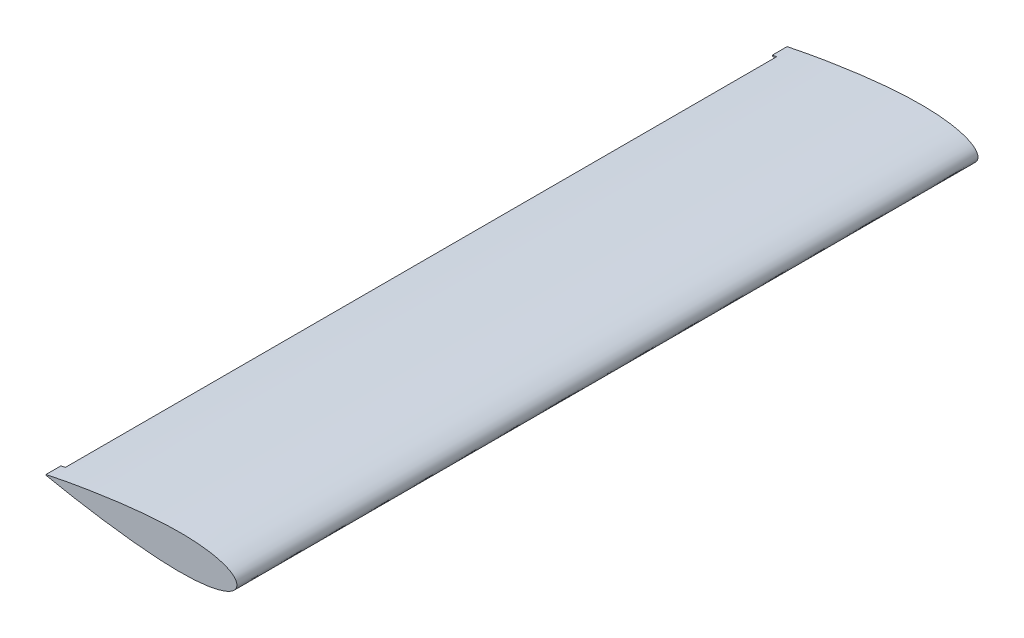
SolidWorks part; units mm, degrees
ref_plane "Alzado" through (0, 0, 0) normal (0, 0, 1) x (1, 0, 0)
ref_plane "Planta" through (0, 0, 0) normal (0, 1, 0) x (1, 0, 0)
ref_plane "Vista lateral" through (0, 0, 0) normal (1, 0, 0) x (0, 0, -1)
sketch "Croquis1" plane through (0, 0, 0) normal (0, 0, 1) x (1, 0, 0)
  line L0 (0, 0) -> (0, -23.5) construction
  line L1 (0, 0) -> (-16, 0) construction
  line L2 (-14.2698, -25.6618) -> (-26, -25.6618)
  line L3 (-26, -25.6618) -> (-26, -33.5)
  line L4 (-26, -33.5) -> (16, -33.5)
  line L5 (16, -33.5) -> (16, 3.8445)
  line L6 (16, 3.8445) -> (-14.2698, 3.8445)
  line L8 (-14.2698, -6.2762) -> (-14.2698, -25.6618)
  line L9 (-14.2698, 3.8445) -> (-26, 3.8445)
  line L10 (-26, 3.8445) -> (-26, -6.2762)
  line L11 (-26, -6.2762) -> (-14.2698, -6.2762)
  circle A0 centre (0, 0) radius 1.5
  dimension "D1" = 3
  dimension "D4" = 16
  dimension "D2" = 23.5
  dimension "D3" = 16
  dimension "D5" = 10
  dimension "D6" = 42
curve "Curva2"
  spline degree 3 poles (266, 0.503, 0) (261.5688, 1.4191, 0) (252.7164, 3.2493, 0) (234.9955, 6.6448, 0) (212.8433, 10.5485, 0) (186.2398, 14.7043, 0) (159.6407, 18.3128, 0) (133.0409, 21.2624, 0) (106.4348, 23.353, 0) (84.237, 24.0962, 0) (66.4893, 23.7999, 0) (53.1677, 23.0109, 0) (39.8211, 21.4881, 0) (28.7128, 19.3599, 0) (19.853, 16.8285, 0) (13.0874, 14.2708, 0) (7.4196, 11.1923, 0) (2.2073, 6.9321, 0) (-1.4404, 0, 0) (2.2073, -6.9321, 0) (7.4196, -11.1923, 0) (13.0874, -14.2708, 0) (19.853, -16.8285, 0) (28.7128, -19.3599, 0) (39.8211, -21.4881, 0) (53.1677, -23.0109, 0) (66.4893, -23.7999, 0) (84.237, -24.0962, 0) (106.4348, -23.353, 0) (133.0409, -21.2624, 0) (159.6407, -18.3128, 0) (186.2398, -14.7043, 0) (212.8433, -10.5485, 0) (234.9955, -6.6448, 0) (252.7164, -3.2493, 0) (261.5688, -1.4191, 0) (266, -0.503, 0) knots 0 0 0 0 0.024604 0.049152 0.098109 0.146905 0.195555 0.244056 0.292409 0.340644 0.364754 0.388905 0.413178 0.437756 0.450305 0.46323 0.477067 0.485036 0.5 0.514964 0.522933 0.53677 0.549695 0.562244 0.586822 0.611095 0.635246 0.659356 0.707591 0.755944 0.804445 0.853095 0.901891 0.950848 0.975396 1 1 1 1
sketch "Croquis6" plane through (0, 0, 0) normal (0, 0, 1) x (1, 0, 0)
  line L2 (-130.0015, 0) -> (0, 0) construction
  line L3 (-65.0007, 0) -> (-65.0007, 10.1736) construction
  line L4 (-128.8232, 0.2436) -> (-130.0015, 0)
  line L5 (-128.8232, -0.2436) -> (-130.0015, 0)
  spline S2 degree 3 poles (-128.8232, 0.2436) (-126.6771, 0.6873) (-122.39, 1.5736) (-113.8077, 3.2181) (-103.0795, 5.1086) (-90.1955, 7.1212) (-77.3136, 8.8689) (-64.4314, 10.2973) (-51.5461, 11.3098) (-40.7958, 11.6698) (-32.2006, 11.5262) (-25.749, 11.1441) (-19.2853, 10.4066) (-13.9056, 9.376) (-9.6147, 8.15) (-6.3382, 6.9113) (-3.5933, 5.4204) (-1.069, 3.3572) (0.6976, 0) (-1.069, -3.3572) (-3.5933, -5.4204) (-6.3382, -6.9113) (-9.6147, -8.15) (-13.9056, -9.376) (-19.2853, -10.4066) (-25.749, -11.1441) (-32.2006, -11.5262) (-40.7958, -11.6698) (-51.5461, -11.3098) (-64.4314, -10.2973) (-77.3136, -8.8689) (-90.1955, -7.1212) (-103.0795, -5.1086) (-113.8077, -3.2181) (-122.39, -1.5736) (-126.6771, -0.6873) (-128.8232, -0.2436) knots 0 0 0 0 0.024604 0.049152 0.098109 0.146905 0.195555 0.244056 0.292409 0.340644 0.364754 0.388905 0.413178 0.437756 0.450305 0.46323 0.477067 0.485036 0.5 0.514964 0.522933 0.53677 0.549695 0.562244 0.586822 0.611095 0.635246 0.659356 0.707591 0.755944 0.804445 0.853095 0.901891 0.950848 0.975396 1 1 1 1
  point P8 (0, 0)
  dimension "D1" = 130.0015
sketch "Croquis7" plane through (0, 0, 0) normal (0, 0, 1) x (1, 0, 0)
  line L0 (-128.8232, 0.2436) -> (-130.0015, 0) construction
  line L1 (-128.8232, 0.2436) -> (-130.0015, 0) construction
  line L2 (-128.8232, -0.2436) -> (-130.0015, 0) construction
  line L3 (-128.8232, -0.2436) -> (-130.0015, 0) construction
  line L4 (-128.8232, -0.2436) -> (-128.8232, 0.2436)
  spline S0 degree 3 poles (-835.2568, 1861.3988) (-332.4561, -82.1992) (-229.4715, -18.9446) (-113.8077, 3.2181) (-103.0795, 5.1086) (-90.1955, 7.1212) (-77.3136, 8.8689) (-64.4314, 10.2973) (-51.5461, 11.3098) (-40.7958, 11.6698) (-32.2006, 11.5262) (-25.749, 11.1441) (-19.2853, 10.4066) (-13.9056, 9.376) (-9.6147, 8.15) (-6.3382, 6.9113) (-3.5933, 5.4204) (-1.069, 3.3572) (0.6976, 0) (-1.069, -3.3572) (-3.5933, -5.4204) (-6.3382, -6.9113) (-9.6147, -8.15) (-13.9056, -9.376) (-19.2853, -10.4066) (-25.749, -11.1441) (-32.2006, -11.5262) (-40.7958, -11.6698) (-51.5461, -11.3098) (-64.4314, -10.2973) (-77.3136, -8.8689) (-90.1955, -7.1212) (-103.0795, -5.1086) (-113.8077, -3.2181) (-229.4717, 18.9446) (-332.4565, 82.1995) (-835.2603, -1861.4125) knots -1.224113 -1.224113 -1.224113 -1.224113 0.024604 0.049152 0.098109 0.146905 0.195555 0.244056 0.292409 0.340644 0.364754 0.388905 0.413178 0.437756 0.450305 0.46323 0.477067 0.485036 0.5 0.514964 0.522933 0.53677 0.549695 0.562244 0.586822 0.611095 0.635246 0.659356 0.707591 0.755944 0.804445 0.853095 0.901891 0.950848 0.975396 2.224116 2.224116 2.224116 2.224116 only from (-128.8232, 0.2436) to (-128.8232, -0.2436) construction
  spline S1 degree 3 poles (-128.8232, 0.2436) (-126.6771, 0.6873) (-122.39, 1.5736) (-113.8077, 3.2181) (-103.0795, 5.1086) (-90.1955, 7.1212) (-77.3136, 8.8689) (-64.4314, 10.2973) (-51.5461, 11.3098) (-40.7958, 11.6698) (-32.2006, 11.5262) (-25.749, 11.1441) (-19.2853, 10.4066) (-13.9056, 9.376) (-9.6147, 8.15) (-6.3382, 6.9113) (-3.5933, 5.4204) (-1.069, 3.3572) (0.6976, 0) (-1.069, -3.3572) (-3.5933, -5.4204) (-6.3382, -6.9113) (-9.6147, -8.15) (-13.9056, -9.376) (-19.2853, -10.4066) (-25.749, -11.1441) (-32.2006, -11.5262) (-40.7958, -11.6698) (-51.5461, -11.3098) (-64.4314, -10.2973) (-77.3136, -8.8689) (-90.1955, -7.1212) (-103.0795, -5.1086) (-113.8077, -3.2181) (-122.39, -1.5736) (-126.6771, -0.6873) (-128.8232, -0.2436) knots 0 0 0 0 0.024604 0.049152 0.098109 0.146905 0.195555 0.244056 0.292409 0.340644 0.364754 0.388905 0.413178 0.437756 0.450305 0.46323 0.477067 0.485036 0.5 0.514964 0.522933 0.53677 0.549695 0.562244 0.586822 0.611095 0.635246 0.659356 0.707591 0.755944 0.804445 0.853095 0.901891 0.950848 0.975396 1 1 1 1
extrude "Saliente-Extruir1" add sketch "Croquis7" along normal mid plane 500
sketch "Croquis8" plane through (0, 0, 0) normal (0, 0, 1) x (1, 0, 0)
  line L0 (-128.9842, -0.6178) -> (-128.9842, 0.6178)
  line L2 (-125.8047, -1.25) -> (-125.8047, 1.25)
  line L4 (-128.8232, 0.2436) -> (-128.8232, -0.2436) construction
  line L5 (-125.8047, 1.25) -> (-128.9842, 0.6178)
  line L6 (-128.9842, -0.6178) -> (-125.8047, -1.25)
  line L7 (-130.0015, 0) -> (0, 0) construction
  point P3 (-128.9842, 0)
  point P6 (-125.8047, 0)
  point P8 (-125.8047, 0)
  point P11 (-128.9842, 0)
  dimension "D1" = 3.0184
  dimension "D2" = 2.5
extrude "Cortar-Extruir1" cut sketch "Croquis8" against normal mid plane 480
